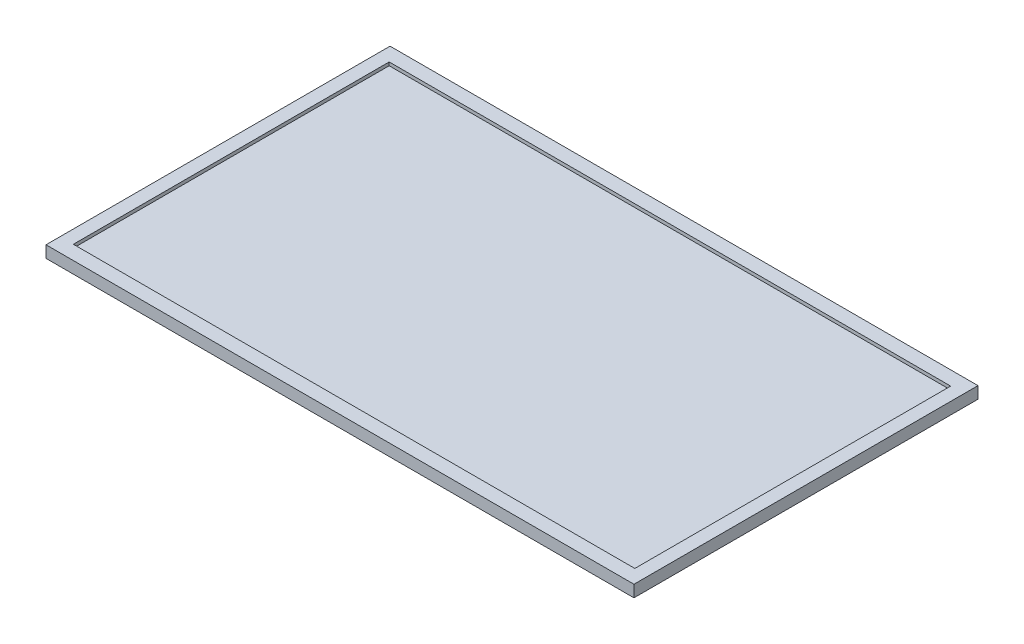
SolidWorks part; units mm, degrees
ref_plane "Alzado" through (0, 0, 0) normal (0, 0, 1) x (1, 0, 0)
ref_plane "Planta" through (0, 0, 0) normal (0, 1, 0) x (1, 0, 0)
ref_plane "Vista lateral" through (0, 0, 0) normal (1, 0, 0) x (0, 0, -1)
sketch "Croquis1" plane through (0, 0, 0) normal (0, 1, 0) x (1, 0, 0)
  line L1 (0, 0) -> (533.2, 0)
  line L2 (0, 0) -> (0, 312)
  line L3 (0, 312) -> (533.2, 312)
  line L4 (533.2, 0) -> (533.2, 312)
  dimension "D1" = 533.2
  dimension "D2" = 312
extrude "Saliente-Extruir1" add sketch "Croquis1" along normal blind 10.7
sketch "Croquis2" plane through (0, 10.7, 0) normal (0, 1, 0) x (1, 0, 0)
  line L0 (533.2, 312) -> (0, 312) construction
  line L1 (12.008, 299.208) -> (521.192, 299.208)
  line L2 (12.008, 299.208) -> (12.008, 12.792)
  line L3 (12.008, 12.792) -> (521.192, 12.792)
  line L4 (521.192, 299.208) -> (521.192, 12.792)
  line L5 (0, 312) -> (0, 0) construction
  point P4 (266.6, 299.208)
  point P7 (266.6, 312)
  point P8 (12.008, 156)
  point P11 (0, 156)
  dimension "D1" = 509.184
  dimension "D2" = 286.416
extrude "Cortar-Extruir1" cut sketch "Croquis2" against normal blind 3
